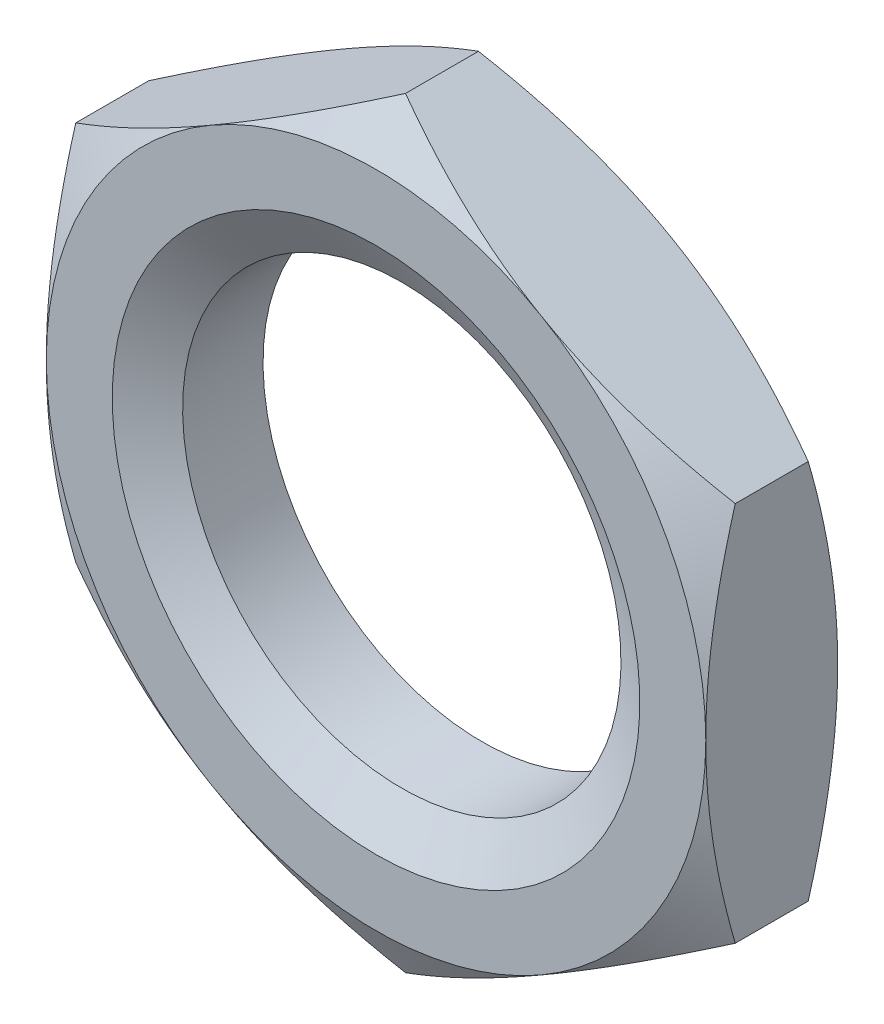
SolidWorks part; units mm, degrees
ref_plane "Front Plane" through (0, 0, 0) normal (0, 0, 1) x (1, 0, 0)
ref_plane "Top Plane" through (0, 0, 0) normal (0, 1, 0) x (1, 0, 0)
ref_plane "Right Plane" through (0, 0, 0) normal (1, 0, 0) x (0, 0, -1)
sketch "Sketch1" plane through (0, 0, 0) normal (0, 0, 1) x (1, 0, 0)
  line L1 (0, 5.7735) -> (-5, 2.8868)
  line L2 (-5, 2.8868) -> (-5, -2.8868)
  line L3 (-5, -2.8868) -> (0, -5.7735)
  line L4 (0, -5.7735) -> (5, -2.8868)
  line L5 (5, -2.8868) -> (5, 2.8868)
  line L6 (5, 2.8868) -> (0, 5.7735)
  circle A0 centre (0, 0) radius 3.3235
  circle A1 centre (0, 0) radius 5 construction
  dimension "D1" = 6.647
  dimension "D2" = 10
extrude "Boss-Extrude1" add sketch "Sketch1" along normal blind 2
sketch "Sketch2" plane through (0, 0, 0) normal (1, 0, 0) x (0, 0, -1)
  line L0 (0, 5.7735) -> (-0.4466, 5.7735)
  line L1 (-2, 5.7735) -> (0, 5.7735) construction
  line L2 (-0.4466, 5.7735) -> (0, 5)
  line L3 (0, 2.8868) -> (0, 5.7735) construction
  line L4 (0, 5) -> (0, 5.7735)
  line L5 (0, 3.3235) -> (0, 4)
  line L6 (0, 4) -> (-0.3906, 3.3235)
  line L7 (-0.3906, 3.3235) -> (0, 3.3235)
  line L8 (0, 0) -> (-1, 0) construction
  line L9 (-1, 0) -> (-1, 5.7735) construction
  line L10 (-1.6094, 3.3235) -> (-2, 3.3235)
  line L11 (-2, 4) -> (-1.6094, 3.3235)
  line L12 (-2, 3.3235) -> (-2, 4)
  line L13 (-2, 5) -> (-2, 5.7735)
  line L14 (-1.5534, 5.7735) -> (-2, 5)
  line L15 (-2, 5.7735) -> (-1.5534, 5.7735)
  dimension "D1" = 10
  dimension "D2" = 30
  dimension "D3" = 8
  dimension "D4" = 60
revolve "Cut-Revolve1" cut sketch "Sketch2" angle 360 about L8
